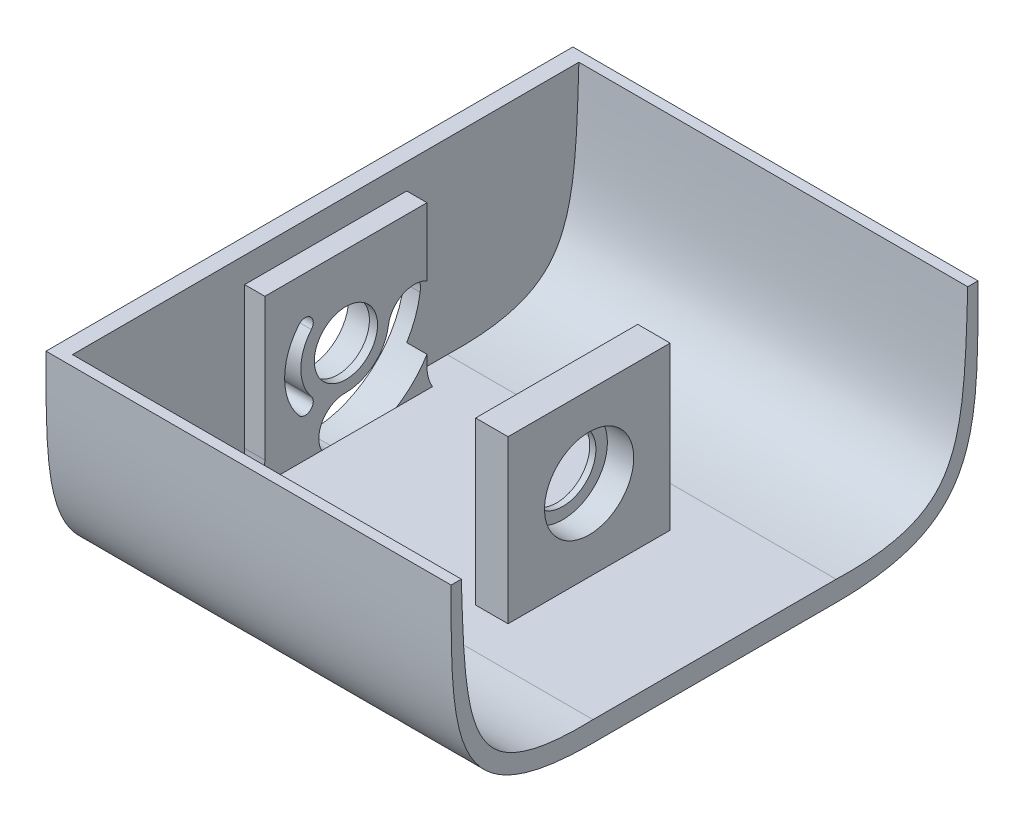
SolidWorks part; units mm, degrees
ref_plane "Plan de face" through (0, 0, 0) normal (0, 0, 1) x (1, 0, 0)
ref_plane "Plan de dessus" through (0, 0, 0) normal (0, 1, 0) x (1, 0, 0)
ref_plane "Plan de droite" through (0, 0, 0) normal (1, 0, 0) x (0, 0, -1)
sketch "Esquisse2" plane through (0, 0, 0) normal (-1, 0, 0) x (0, 0, 1)
  line L0 (142.8834, 43.5601) -> (142.8834, 28.5601)
  line L2 (182.8834, 43.5601) -> (182.8834, 28.5601)
  line L3 (132.8834, 18.5601) -> (192.8834, 18.5601)
  line L4 (162.8834, 23.5601) -> (-2.794, 6) construction
  line L5 (142.8834, 28.5601) -> (190.6953, 28.5601) construction
  line L8 (142.8834, 43.5601) -> (142.8834, 63.5386)
  line L9 (142.8834, 63.5386) -> (182.8834, 63.5386)
  line L10 (182.8834, 43.5601) -> (182.8834, 63.5386)
  arc A1 (142.8834, 43.5601) -> (149.6547, 28.5601) centre (162.8834, 43.5601) ccw
  arc A2 (182.8834, 28.5601) -> (192.8834, 18.5601) centre (192.8834, 28.5601) ccw
  arc A3 (132.8834, 18.5601) -> (142.8834, 28.5601) centre (132.8834, 28.5601) ccw
  circle A4 centre (162.8834, 43.5601) radius 26.2575 construction
  arc A5 (163.8107, 63.5386) -> (161.9562, 63.5386) centre (162.8834, 43.5601) ccw
  point P16 (17.206, 6)
  point P19 (-22.794, 6)
  dimension "D1" = 40
  dimension "D2" = 10
  dimension "D3" = 25
extrude "Boss.-Extru.2" add sketch "Esquisse2" against normal blind 9
sketch "Esquisse3" plane through (0, 0, 0) normal (-1, 0, 0) x (0, 0, 1)
  circle A0 centre (162.8834, 43.5601) radius 9.6446
extrude "Enlèv. mat.-Extru.1" cut sketch "Esquisse3" against normal blind 7
sketch "Esquisse5" plane through (9, 0, 0) normal (1, 0, 0) x (0, 0, -1)
  circle A0 centre (-162.8834, 43.5601) radius 7.8
extrude "Enlèv. mat.-Extru.2" cut sketch "Esquisse5" against normal blind 6
sketch "Esquisse6" plane through (0, 18.5601, 0) normal (0, -1, 0) x (1, 0, 0)
  line L0 (99.9485, 162.8834) -> (9, 162.8834) construction
  line L1 (0, 132.8834) -> (99.9485, 132.8834)
  line L2 (0, 132.8834) -> (0, 192.8834)
  line L3 (0, 192.8834) -> (99.9485, 192.8834)
  line L4 (99.9485, 132.8834) -> (99.9485, 192.8834)
  line L7 (9, 132.8834) -> (9, 192.8834) construction
  dimension "D1" = 60
extrude "Boss.-Extru.3" add sketch "Esquisse6" against normal blind 5
ref_plane "Plan1" through (69, 0, 0) normal (1, 0, 0) x (0, 0, -1)
sketch "Esquisse7" plane through (69, 0, 0) normal (1, 0, 0) x (0, 0, -1)
  line L0 (-132.8834, 23.5601) -> (-192.8834, 23.5601) construction
  line L1 (-182.8834, 63.5386) -> (-142.8834, 63.5386)
  line L2 (-182.8834, 63.5386) -> (-182.8834, 23.5601)
  line L3 (-182.8834, 23.5601) -> (-142.8834, 23.5601)
  line L4 (-142.8834, 63.5386) -> (-142.8834, 23.5601)
extrude "Boss.-Extru.4" add sketch "Esquisse7" against normal blind 8
sketch "Esquisse8" plane through (69, 0, 0) normal (1, 0, 0) x (0, 0, -1)
  circle A0 centre (-162.8834, 43.5601) radius 11
extrude "Enlèv. mat.-Extru.3" cut sketch "Esquisse8" against normal up to surface (6.4839 mm away)
sketch "Esquisse9" plane through (61, 0, 0) normal (-1, 0, 0) x (0, 0, 1)
  circle A0 centre (162.8834, 43.5601) radius 8.1652
extrude "Enlèv. mat.-Extru.4" cut sketch "Esquisse9" against normal blind 5
sketch "Esquisse10" plane through (99.9485, 0, 0) normal (1, 0, 0) x (0, 0, -1)
  line L0 (-97.8834, 23.5601) -> (-97.8834, 74.8177) construction
  line L1 (-227.8834, 23.5601) -> (-227.8834, 74.8177) construction
  line L2 (-227.8834, 74.8177) -> (-97.8834, 74.8177) construction
  line L3 (-162.8834, 69.8177) -> (-181.9862, 69.8177) construction
  line L4 (-100.4102, 69.8177) -> (-225.3567, 69.8177) construction
  line L9 (-100.4102, 69.8177) -> (-97.8834, 69.8177)
  line L11 (-162.8834, 74.8177) -> (-162.8834, 18.5601) construction
  line L12 (-132.8834, 18.5601) -> (-192.8834, 18.5601)
  line L13 (-132.8834, 23.5601) -> (-192.8834, 23.5601)
  line L17 (-227.8834, 69.8177) -> (-225.3567, 69.8177)
  arc A0 (-138.3561, 52.934) -> (-185.21, 29.7403) centre (-162.8834, 43.5601) ccw construction
  spline S0 degree 3 poles (-97.8834, 69.8177) (-97.8834, 36.968) (-97.4284, 18.5601) (-132.8834, 18.5601) knots 0 0 0 0 1 1 1 1
  spline S1 degree 3 poles (-227.8834, 69.8177) (-227.8834, 36.968) (-228.3385, 18.5601) (-192.8834, 18.5601) knots 0 0 0 0 1 1 1 1
  spline S4 degree 3 poles (-100.4102, 69.8177) (-100.442, 68.8061) (-100.5056, 66.76) (-100.6324, 62.8505) (-100.8103, 58.1851) (-101.1051, 52.996) (-101.6706, 46.6332) (-102.818, 39.7765) (-104.7653, 34.5276) (-106.8658, 31.2487) (-108.7564, 29.178) (-111.0592, 27.4237) (-113.9094, 25.9503) (-117.1434, 24.8725) (-119.9404, 24.2902) (-122.2331, 23.9495) (-124.2609, 23.7266) (-126.9008, 23.5593) (-129.2903, 23.507) (-131.3015, 23.5189) (-132.3607, 23.5436) (-132.8834, 23.5601) knots 0 0 0 0 0.03125 0.0625 0.125 0.1875 0.25 0.375 0.5 0.5625 0.625 0.6875 0.75 0.8125 0.85971 0.875335 0.90625 0.9375 0.96875 0.984375 1 1 1 1
  spline S5 degree 3 poles (-192.8834, 23.5601) (-193.4062, 23.5436) (-194.4654, 23.5189) (-196.4766, 23.507) (-198.8661, 23.5593) (-201.5059, 23.7266) (-203.5337, 23.9495) (-205.8265, 24.2902) (-208.6235, 24.8725) (-211.8575, 25.9503) (-214.7077, 27.4237) (-217.0105, 29.178) (-218.9011, 31.2487) (-221.0016, 34.5276) (-222.9489, 39.7765) (-224.0963, 46.6332) (-224.6618, 52.996) (-224.9566, 58.1851) (-225.1345, 62.8505) (-225.2613, 66.76) (-225.3249, 68.8061) (-225.3567, 69.8177) knots 0 0 0 0 0.015625 0.03125 0.0625 0.09375 0.124664 0.140289 0.1875 0.25 0.3125 0.375 0.4375 0.5 0.625 0.75 0.8125 0.875 0.9375 0.96875 1 1 1 1
  point P15 (-132.8834, 22.5601)
extrude "Boss.-Extru.5" add sketch "Esquisse10" against normal up to surface (99.9485 mm away) up to face at (0, 43.5601, 172.5281)
sketch "Esquisse11" plane through (0, 0, 0) normal (-1, 0, 0) x (0, 0, 1)
  line L0 (225.3567, 69.8177) -> (100.4102, 69.8177)
  line L8 (141.5437, 23.5601) -> (132.8834, 23.5601)
  line L9 (100.4102, 69.8177) -> (97.8834, 69.8177)
  line L10 (132.8834, 18.5601) -> (192.8834, 18.5601)
  line L11 (227.8834, 69.8177) -> (225.3567, 69.8177)
  line L12 (192.8834, 23.5601) -> (184.2232, 23.5601)
  line L13 (182.8834, 28.5601) -> (182.8834, 63.5386)
  line L14 (182.8834, 63.5386) -> (142.8834, 63.5386)
  line L15 (142.8834, 63.5386) -> (142.8834, 28.5601)
  line L17 (100.4102, 69.8177) -> (97.8834, 69.8177)
  line L18 (132.8834, 18.5601) -> (192.8834, 18.5601)
  line L19 (227.8834, 69.8177) -> (225.3567, 69.8177)
  line L22 (182.8834, 63.5386) -> (142.8834, 63.5386)
  arc A2 (141.5437, 23.5601) -> (142.8834, 28.5601) centre (132.8834, 28.5601) ccw
  arc A3 (182.8834, 28.5601) -> (184.2232, 23.5601) centre (192.8834, 28.5601) ccw
  spline S4 degree 3 poles (-867.0242, 12.321) (189.9568, 30.895) (149.9174, 23.6293) (129.2903, 23.507) (126.9008, 23.5593) (124.2609, 23.7266) (122.2331, 23.9495) (119.9404, 24.2902) (117.1434, 24.8725) (113.9094, 25.9503) (111.0592, 27.4237) (108.7564, 29.178) (106.8658, 31.2487) (104.7653, 34.5276) (102.818, 39.7765) (101.6706, 46.6332) (101.1051, 52.996) (100.8103, 58.1851) (100.6324, 62.8505) (99.51, 97.4672) (98.3904, 155.6109) (96.214, -930.1621) knots -0.578513 -0.578513 -0.578513 -0.578513 0.015625 0.03125 0.0625 0.09375 0.124665 0.14029 0.1875 0.25 0.3125 0.375 0.4375 0.5 0.625 0.75 0.8125 0.875 0.9375 0.96875 1.981799 1.981799 1.981799 1.981799 only from (132.8834, 23.5601) to (100.4102, 69.8177)
  spline S5 degree 3 poles (-2711.4654, 965.8864) (2949.138, 245.1665) (-2795.8041, -652.2852) (3034.5349, 779.8405) knots -4.246513 -4.246513 -4.246513 -4.246513 4.334923 4.334923 4.334923 4.334923 only from (97.8834, 69.8177) to (132.8834, 18.5601)
  spline S6 degree 3 poles (-2708.6613, 779.8143) (3121.5094, -652.2763) (-2623.3534, 245.1735) (3037.2572, 965.8895) knots -3.33487 -3.33487 -3.33487 -3.33487 5.246526 5.246526 5.246526 5.246526 only from (192.8834, 18.5601) to (227.8834, 69.8177)
  spline S7 degree 3 poles (229.553, -930.1715) (227.3765, 155.6112) (226.2569, 97.4673) (225.1345, 62.8505) (224.9566, 58.1851) (224.6618, 52.996) (224.0963, 46.6332) (222.9489, 39.7765) (221.0016, 34.5276) (218.9011, 31.2487) (217.0105, 29.178) (214.7077, 27.4237) (211.8575, 25.9503) (208.6235, 24.8725) (205.8265, 24.2902) (203.5337, 23.9495) (201.5059, 23.7266) (198.8661, 23.5593) (196.4766, 23.507) (175.8499, 23.6293) (135.8116, 30.8948) (1192.7309, 12.322) knots -0.981802 -0.981802 -0.981802 -0.981802 0.03125 0.0625 0.125 0.1875 0.25 0.375 0.5 0.5625 0.625 0.6875 0.75 0.8125 0.859711 0.875336 0.90625 0.9375 0.96875 0.984375 1.578501 1.578501 1.578501 1.578501 only from (225.3567, 69.8177) to (192.8834, 23.5601)
  spline S9 degree 3 poles (97.8834, 69.8177) (97.8834, 36.968) (97.4284, 18.5601) (132.8834, 18.5601) knots 0 0 0 0 1 1 1 1
  spline S10 degree 3 poles (192.8834, 18.5601) (228.3385, 18.5601) (227.8834, 36.968) (227.8834, 69.8177) knots 0 0 0 0 1 1 1 1
  arc M16 (142.8834, 28.5601) -> (141.5437, 23.5601) centre (132.8834, 28.5601) cw
  line M17 (141.5437, 23.5601) -> (132.8834, 23.5601)
  spline M18 degree 3 poles (100.4102, 69.8177) (100.442, 68.8061) (100.5056, 66.76) (100.6324, 62.8505) (100.8103, 58.1851) (101.1051, 52.996) (101.6706, 46.6332) (102.818, 39.7765) (104.7653, 34.5276) (106.8658, 31.2487) (108.7564, 29.178) (111.0592, 27.4237) (113.9094, 25.9503) (117.1434, 24.8725) (119.9404, 24.2902) (122.2331, 23.9495) (124.2609, 23.7266) (126.9008, 23.5593) (129.2903, 23.507) (131.3015, 23.5189) (132.3607, 23.5436) (132.8834, 23.5601) knots 0 0 0 0 0.03125 0.0625 0.125 0.1875 0.25 0.375 0.5 0.5625 0.625 0.6875 0.75 0.8125 0.85971 0.875335 0.90625 0.9375 0.96875 0.984375 1 1 1 1
  spline M24 degree 3 poles (192.8834, 23.5601) (193.4062, 23.5436) (194.4654, 23.5189) (196.4766, 23.507) (198.8661, 23.5593) (201.5059, 23.7266) (203.5337, 23.9495) (205.8265, 24.2902) (208.6235, 24.8725) (211.8575, 25.9503) (214.7077, 27.4237) (217.0105, 29.178) (218.9011, 31.2487) (221.0016, 34.5276) (222.9489, 39.7765) (224.0963, 46.6332) (224.6618, 52.996) (224.9566, 58.1851) (225.1345, 62.8505) (225.2613, 66.76) (225.3249, 68.8061) (225.3567, 69.8177) knots 0 0 0 0 0.015625 0.03125 0.0625 0.09375 0.124664 0.140289 0.1875 0.25 0.3125 0.375 0.4375 0.5 0.625 0.75 0.8125 0.875 0.9375 0.96875 1 1 1 1
  line M25 (192.8834, 23.5601) -> (184.2232, 23.5601)
  arc M26 (184.2232, 23.5601) -> (182.8834, 28.5601) centre (192.8834, 28.5601) cw
  line M27 (182.8834, 28.5601) -> (182.8834, 63.5386)
  line M28 (182.8834, 63.5386) -> (142.8834, 63.5386)
  line M29 (142.8834, 63.5386) -> (142.8834, 28.5601)
  dimension "D1" = 0
extrude "Boss.-Extru.6" add sketch "Esquisse11" against normal blind 4 contours L0 M24 M18 M17 M16 M29 M28 M27 M26 M25
sketch "Esquisse12" plane through (0, 0, 0) normal (-1, 0, 0) x (0, 0, 1)
  line L0 (162.8834, 43.5601) -> (128.9886, 3.1658) construction
  line L1 (128.9886, 3.1658) -> (196.7783, 3.1658) construction
  line L2 (196.7783, 3.1658) -> (162.8834, 43.5601) construction
  line L3 (162.8834, 43.5601) -> (162.8834, 3.1658) construction
  line L4 (194.565, 16.9761) -> (194.565, 70.1441) construction
  line L5 (194.565, 70.1441) -> (162.8834, 43.5601) construction
  line L6 (162.8834, 43.5601) -> (194.565, 16.9761) construction
  line L7 (194.565, 43.5601) -> (162.8834, 43.5601) construction
  arc A0 (152.4002, 42.0784) -> (163.0147, 32.9735) centre (162.8834, 43.5601) ccw
  arc A1 (139.5736, 40.2654) -> (163.1753, 20.0204) centre (162.8834, 43.5601) ccw
  arc A2 (163.1753, 20.0204) -> (163.0147, 32.9735) centre (163.095, 26.4969) ccw
  circle A3 centre (162.8834, 43.5601) radius 13.1288 construction
  arc A5 (171.4086, 36.4067) -> (174.4728, 33.8355) centre (172.9407, 35.1211) ccw
  arc A6 (174.4728, 53.2847) -> (171.4086, 50.7136) centre (172.9407, 51.9991) ccw
  arc A7 (171.4086, 36.4067) -> (171.4086, 50.7136) centre (162.8834, 43.5601) ccw
  arc A8 (174.4728, 33.8355) -> (174.4728, 53.2847) centre (162.8834, 43.5601) ccw
  arc A9 (151.2737, 37.43) -> (139.5736, 40.2654) centre (145.9869, 41.1719) ccw
  dimension "D1" = 80
  dimension "D4" = 4
  dimension "D2" = 80
extrude "Enlèv. mat.-Extru.5" cut sketch "Esquisse12" against normal up to surface (9 mm away)
